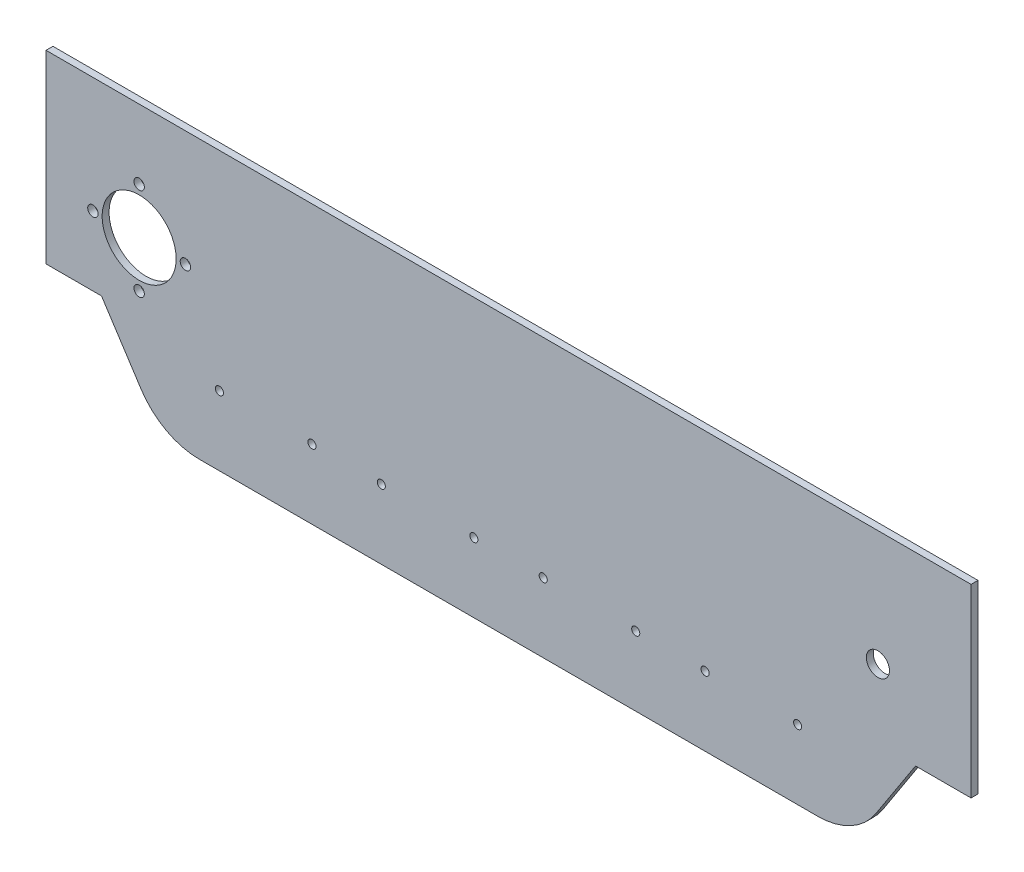
SolidWorks part; units mm, degrees
ref_plane "前基準面" through (0, 0, 0) normal (0, 0, 1) x (1, 0, 0)
ref_plane "上基準面" through (0, 0, 0) normal (0, 1, 0) x (1, 0, 0)
ref_plane "右基準面" through (0, 0, 0) normal (1, 0, 0) x (0, 0, -1)
sketch "草圖1" plane through (0, 0, 0) normal (0, 0, 1) x (1, 0, 0)
  line L0 (55.2806, 100) -> (374.7194, 100)
  line L1 (0, 0) -> (430, 0) construction
  line L2 (0, 0) -> (0, 100) construction
  line L3 (0, 100) -> (430, 100) construction
  line L4 (430, 0) -> (430, 100) construction
  line L5 (399.8727, 53.6503) -> (373.8727, 13.6503)
  line L6 (348.7194, 0) -> (81.2806, 0)
  line L7 (56.1273, 13.6503) -> (30.1273, 53.6503)
  line L8 (215, 0) -> (215, 100) construction
  arc A0 (55.2806, 100) -> (30.1273, 53.6503) centre (55.2806, 70) ccw
  arc A1 (81.2806, 0) -> (56.1273, 13.6503) centre (81.2806, 30) cw
  arc A2 (374.7194, 100) -> (399.8727, 53.6503) centre (374.7194, 70) cw
  arc A3 (373.8727, 13.6503) -> (348.7194, 0) centre (348.7194, 30) cw
  point P14 (65, 0)
  point P20 (365, 0)
  dimension "D4" = 30
  dimension "D1" = 430
  dimension "D2" = 100
  dimension "D3" = 300
extrude "伸長1" add sketch "草圖1" along normal blind 3
sketch "草圖2" plane through (0, 0, 3) normal (0, 0, 1) x (1, 0, 0)
  line L0 (110, 35) -> (210, 35) construction
  line L1 (80, 50) -> (140, 50)
  line L2 (80, 50) -> (80, 20)
  line L3 (80, 20) -> (140, 20)
  line L4 (140, 50) -> (140, 20)
  line L5 (80, 50) -> (140, 20) construction
  line L6 (80, 20) -> (140, 50) construction
  line L7 (150, 50) -> (210, 50)
  line L8 (150, 50) -> (150, 20)
  line L9 (150, 20) -> (210, 20)
  line L10 (210, 50) -> (210, 20)
  line L11 (150, 50) -> (210, 20) construction
  line L12 (150, 20) -> (210, 50) construction
  line L13 (220, 50) -> (280, 50)
  line L14 (220, 50) -> (220, 20)
  line L15 (220, 20) -> (280, 20)
  line L16 (280, 50) -> (280, 20)
  line L17 (220, 50) -> (280, 20) construction
  line L18 (220, 20) -> (280, 50) construction
  line L19 (210, 35) -> (250, 35) construction
  line L20 (140, 50) -> (150, 50) construction
  line L21 (210, 50) -> (220, 50) construction
  line L22 (215, 100) -> (215, 0) construction
  line L23 (250, 35) -> (320, 35) construction
  line L24 (280, 20) -> (290, 20) construction
  line L25 (140, 20) -> (150, 20) construction
  line L26 (210, 20) -> (220, 20) construction
  line L27 (374.7194, 100) -> (55.2806, 100) construction
  line L28 (81.2806, 0) -> (348.7194, 0) construction
  line L29 (280, 50) -> (290, 50) construction
  line L30 (215, 50) -> (215, 80.2047) construction
  line L31 (350, 20) -> (290, 20)
  line L32 (350, 20) -> (350, 50)
  line L33 (350, 50) -> (290, 50)
  line L34 (290, 20) -> (290, 50)
  line L35 (350, 20) -> (290, 50) construction
  line L36 (350, 50) -> (290, 20) construction
  point P0 (110, 35)
  point P10 (250, 35)
  dimension "D1" = 30
  dimension "D2" = 60
  dimension "D3" = 20
  dimension "D4" = 10
sketch "草圖3" plane through (0, 0, 3) normal (0, 0, 1) x (1, 0, 0)
  line L0 (55.2806, 70) -> (374.7194, 70) construction
  line L1 (55.2806, 70) -> (35.2806, 70) construction
  line L2 (374.7194, 70) -> (394.7194, 70) construction
  line L4 (374.7194, 90) -> (374.7194, 50) construction
  line L6 (55.2806, 90) -> (55.2806, 50) construction
  circle A0 centre (55.2806, 70) radius 20 construction
  circle A1 centre (374.7194, 70) radius 20 construction
  circle A2 centre (55.2806, 70) radius 16
  circle A3 centre (374.7194, 70) radius 16 construction
  circle A4 centre (55.2806, 90) radius 2.25
  circle A5 centre (75.2806, 70) radius 2.25
  circle A6 centre (55.2806, 50) radius 2.25
  circle A7 centre (35.2806, 70) radius 2.25
  circle A8 centre (374.7194, 50) radius 2.25 construction
  circle A9 centre (394.7194, 70) radius 2.25 construction
  circle A10 centre (374.7194, 90) radius 2.25 construction
  circle A11 centre (354.7194, 70) radius 2.25 construction
  circle A12 centre (374.7194, 70) radius 5
  dimension "D1" = 40
  dimension "D2" = 32
  dimension "D3" = 4.5
  dimension "D4" = 10
extrude "伸長3" cut sketch "草圖3" against normal through all
sketch "草圖4" plane through (0, 0, 3) normal (0, 0, 1) x (1, 0, 0)
  line L0 (373.8727, 13.6503) -> (399.8727, 53.6503) construction
  line L1 (30.1273, 53.6503) -> (56.1273, 13.6503) construction
  line L2 (374.7194, 100) -> (55.2806, 100) construction
  line L3 (391, 40) -> (399.8727, 53.6503)
  line L4 (30.1273, 53.6503) -> (39, 40)
  line L5 (374.7194, 100) -> (55.2806, 100)
  line L6 (15, 40) -> (415, 40) construction
  line L7 (15, 40) -> (15, 120)
  line L8 (15, 120) -> (415, 120)
  line L9 (415, 120) -> (415, 40)
  line L10 (81.2806, 0) -> (348.7194, 0) construction
  line L11 (215, 120) -> (215, 100) construction
  line L12 (15, 40) -> (39, 40)
  line L13 (415, 40) -> (391, 40)
  arc A1 (399.8727, 53.6503) -> (374.7194, 100) centre (374.7194, 70) ccw construction
  arc A2 (55.2806, 100) -> (30.1273, 53.6503) centre (55.2806, 70) ccw construction
  circle A3 centre (55.2806, 70) radius 16 construction
  arc A5 (399.8727, 53.6503) -> (374.7194, 100) centre (374.7194, 70) ccw
  arc A6 (55.2806, 100) -> (30.1273, 53.6503) centre (55.2806, 70) ccw
  circle A7 centre (55.2806, 70) radius 16
  dimension "D1" = 400
  dimension "D2" = 20
  dimension "D3" = 80
extrude "伸長4" add sketch "草圖4" against normal blind 3
sketch "草圖5" plane through (0, 0, 3) normal (0, 0, 1) x (1, 0, 0)
  line L0 (140, 20) -> (140, 30) construction
  line L1 (140, 30) -> (80, 30) construction
  line L5 (80, 50) -> (80, 20) construction
  line L6 (140, 50) -> (140, 20) construction
  circle A0 centre (130, 30) radius 1.75
  circle A1 centre (90, 30) radius 1.75
  dimension "D4" = 3.5
  dimension "D1" = 10
  dimension "D2" = 10
  dimension "D3" = 10
extrude "伸長5" cut sketch "草圖5" against normal through all
pattern_linear "直線複製排列1" count 4 spacing 70 along (1, 0, 0) of "伸長5"
